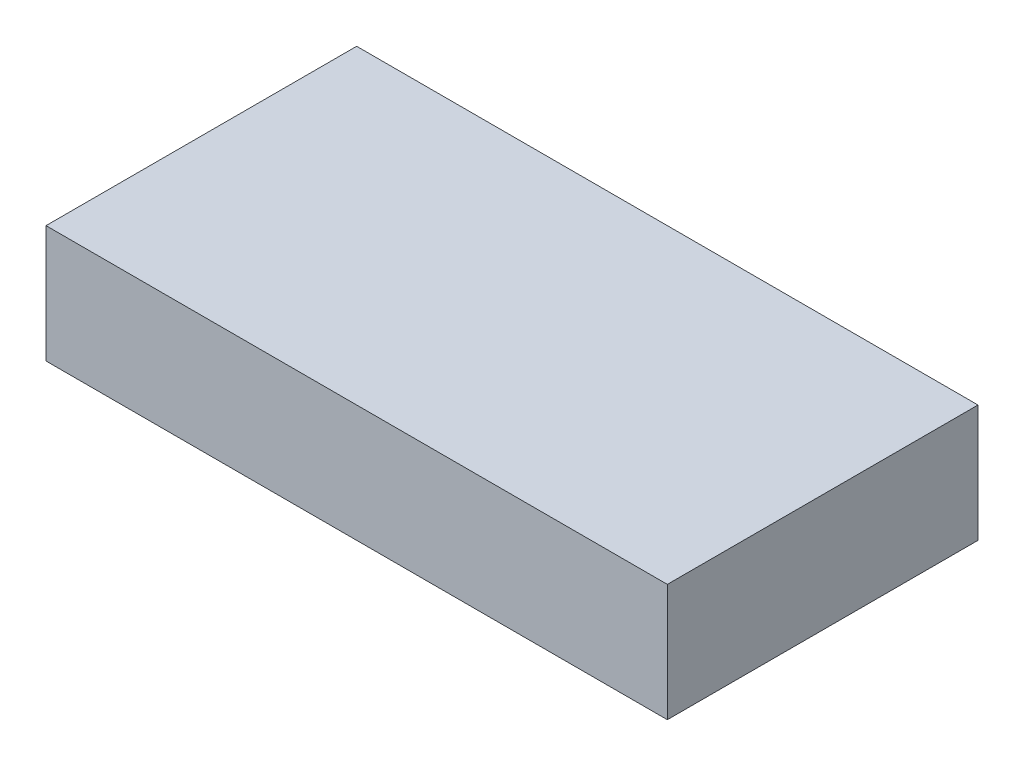
SolidWorks part; units mm, degrees
ref_plane "Front Plane" through (0, 0, 0) normal (0, 0, 1) x (1, 0, 0)
ref_plane "Top Plane" through (0, 0, 0) normal (0, 1, 0) x (1, 0, 0)
ref_plane "Right Plane" through (0, 0, 0) normal (1, 0, 0) x (0, 0, -1)
sketch "Sketch1" plane through (0, 0, 0) normal (0, 1, 0) x (1, 0, 0)
  line L1 (0, 0) -> (15.9, 0)
  line L2 (0, 0) -> (0, -7.95)
  line L3 (0, -7.95) -> (15.9, -7.95)
  line L4 (15.9, 0) -> (15.9, -7.95)
  dimension "D1" = 7.95
  dimension "D2" = 15.9
extrude "Boss-Extrude1" add sketch "Sketch1" along normal blind 3
sketch "Sketch2" plane through (0, 0, 0) normal (0, -1, 0) x (1, 0, 0)
  line L0 (0, 7.95) -> (15.9, 0) construction
  line L1 (15.9, 0) -> (15.9, 7.95) construction
  line L2 (15.9, 7.95) -> (0, 0) construction
  line L3 (0, 7.95) -> (15.9, 7.95) construction
  line L4 (1.5, 6.45) -> (14.4, 6.45)
  line L5 (1.5, 6.45) -> (1.5, 1.5)
  line L6 (1.5, 1.5) -> (14.4, 1.5)
  line L7 (14.4, 6.45) -> (14.4, 1.5)
  line L8 (1.5, 6.45) -> (14.4, 1.5) construction
  line L9 (1.5, 1.5) -> (14.4, 6.45) construction
  line L10 (0, 0) -> (0, 7.95) construction
  point P4 (7.95, 3.975)
  point P15 (0, 3.975)
  dimension "D1" = 1.5
  dimension "D2" = 1.5
extrude "Cut-Extrude1" cut sketch "Sketch2" against normal blind 2
